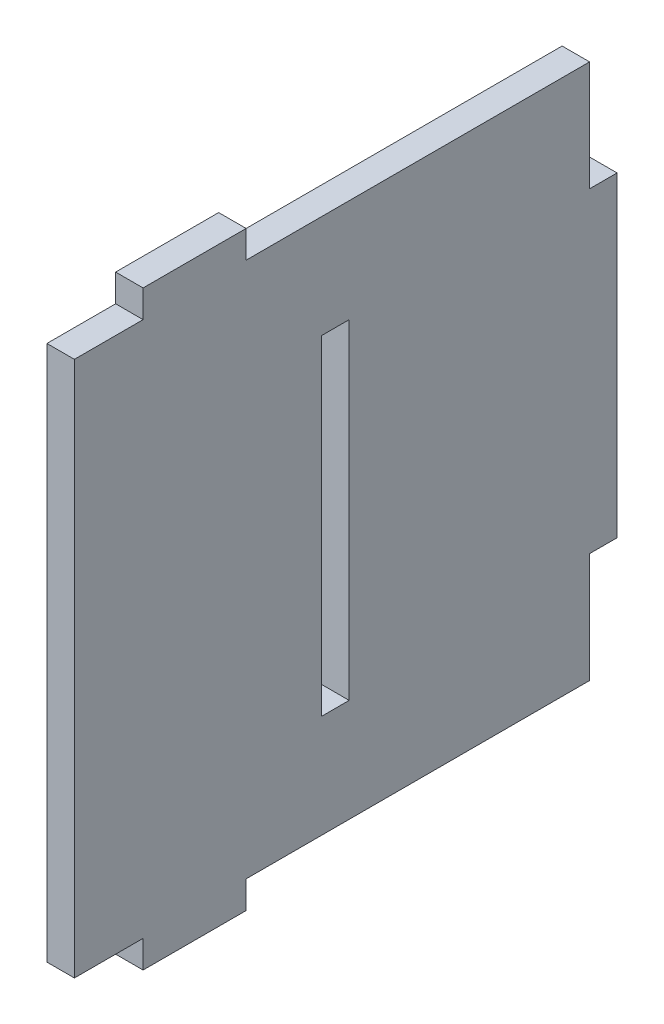
SolidWorks part; units mm, degrees
ref_plane "Front Plane" through (0, 0, 0) normal (0, 0, 1) x (1, 0, 0)
ref_plane "Top Plane" through (0, 0, 0) normal (0, 1, 0) x (1, 0, 0)
ref_plane "Right Plane" through (0, 0, 0) normal (1, 0, 0) x (0, 0, -1)
sketch "Sketch1" plane through (0, 0, 0) normal (1, 0, 0) x (0, 0, -1)
  line L0 (10, 0) -> (10, -4)
  line L1 (0, 0) -> (10, 0)
  line L2 (0, 0) -> (0, 78)
  line L3 (0, 78) -> (10, 78)
  line L4 (75, 0) -> (75, 16)
  line L5 (10, -4) -> (25, -4)
  line L6 (25, -4) -> (25, 0)
  line L7 (25, 0) -> (75, 0)
  line L8 (10, 78) -> (10, 82)
  line L9 (36, 15) -> (40, 15)
  line L10 (36, 15) -> (36, 63)
  line L11 (36, 63) -> (40, 63)
  line L12 (40, 15) -> (40, 63)
  line L13 (10, 82) -> (25, 82)
  line L14 (25, 82) -> (25, 78)
  line L15 (25, 78) -> (75, 78)
  line L16 (75, 62) -> (75, 78)
  line L17 (75, 62) -> (79, 62)
  line L19 (75, 16) -> (79, 16)
  line L20 (79, 62) -> (79, 16)
  dimension "D1" = 78
  dimension "D3" = 4
  dimension "D4" = 10
  dimension "D5" = 15
  dimension "D6" = 4
  dimension "D7" = 36
  dimension "D8" = 15
  dimension "D9" = 15
  dimension "D10" = 4
  dimension "D2" = 35
  dimension "D11" = 4
  dimension "D12" = 16
  dimension "D13" = 16
extrude "Boss-Extrude1" add sketch "Sketch1" along normal blind 4
equation "\"D10@Sketch1\"=\"D3@Sketch1\""
